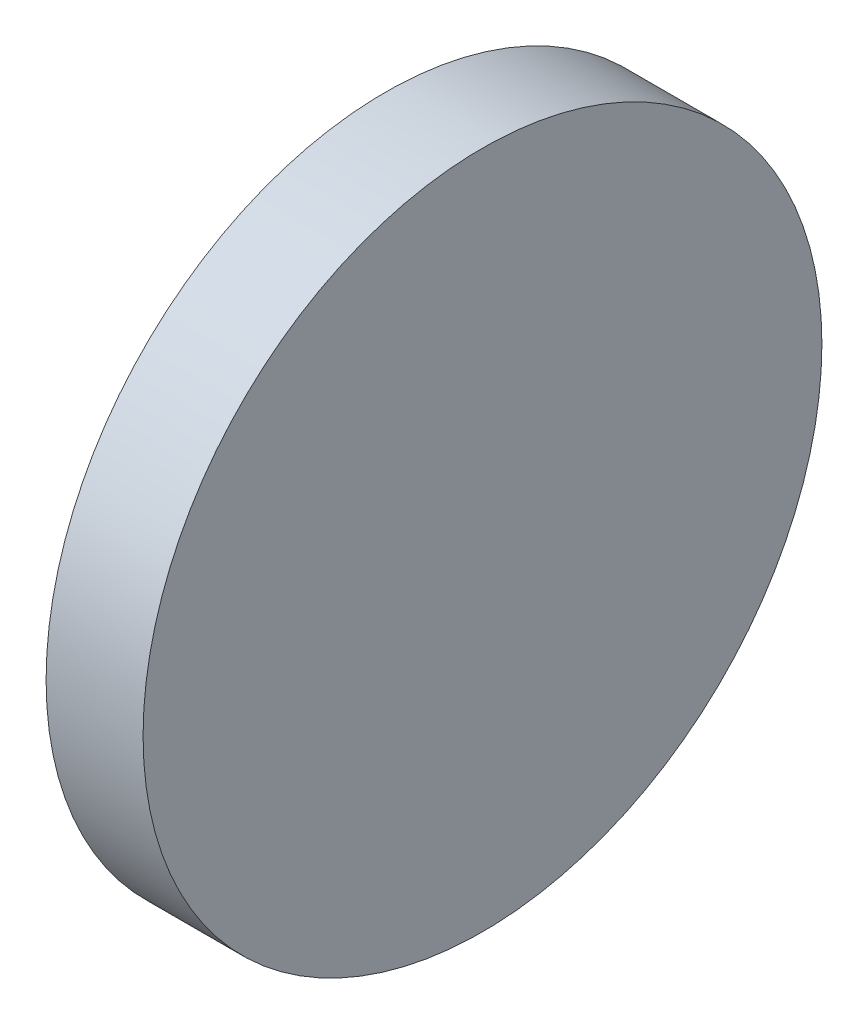
SolidWorks part; units mm, degrees
ref_plane "Front Plane" through (0, 0, 0) normal (0, 0, 1) x (1, 0, 0)
ref_plane "Top Plane" through (0, 0, 0) normal (0, 1, 0) x (1, 0, 0)
ref_plane "Right Plane" through (0, 0, 0) normal (1, 0, 0) x (0, 0, -1)
sketch "Sketch1" plane through (0, 0, 0) normal (1, 0, 0) x (0, 0, -1)
  circle A0 centre (0, 0) radius 35
  dimension "D1" = 70
extrude "Boss-Extrude1" add sketch "Sketch1" against normal blind 10 contours A0
